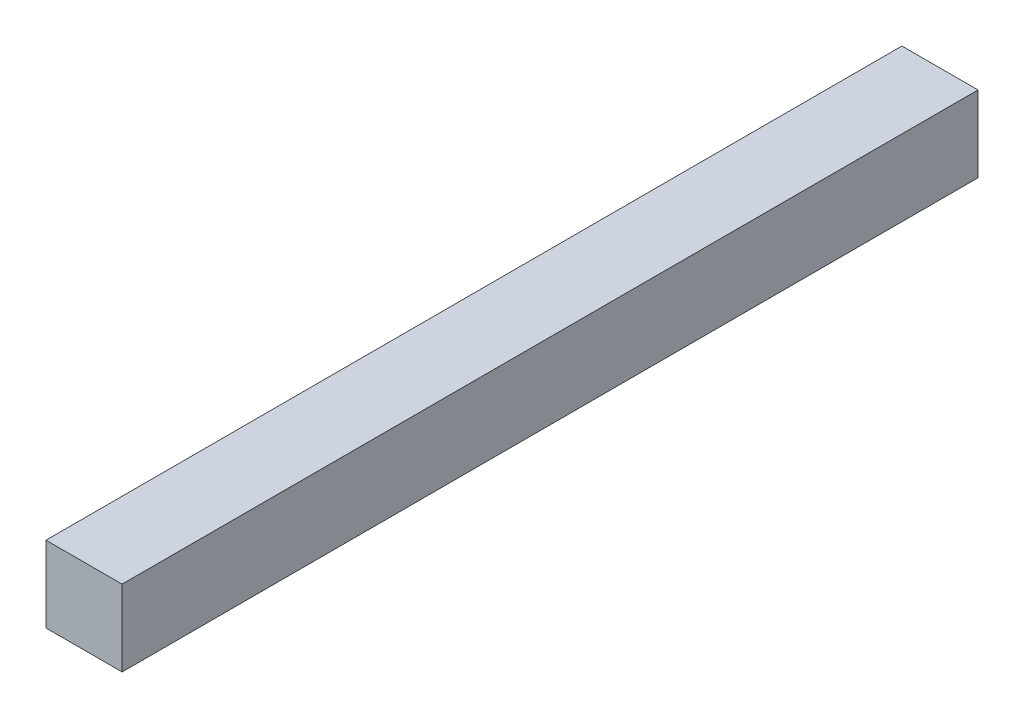
SolidWorks part; units mm, degrees
material "Pine"
ref_plane "Front Plane" through (0, 0, 0) normal (0, 0, 1) x (1, 0, 0)
ref_plane "Top Plane" through (0, 0, 0) normal (0, 1, 0) x (1, 0, 0)
ref_plane "Right Plane" through (0, 0, 0) normal (1, 0, 0) x (0, 0, -1)
sketch "Sketch1" plane through (0, 0, 0) normal (0, 0, 1) x (1, 0, 0)
  line L1 (0, 0) -> (88.9, 0)
  line L2 (0, 0) -> (0, 88.9)
  line L3 (0, 88.9) -> (88.9, 88.9)
  line L4 (88.9, 0) -> (88.9, 88.9)
  dimension "D1" = 88.9
  dimension "D2" = 88.9
extrude "Boss-Extrude1" add sketch "Sketch1" along normal blind 1000
